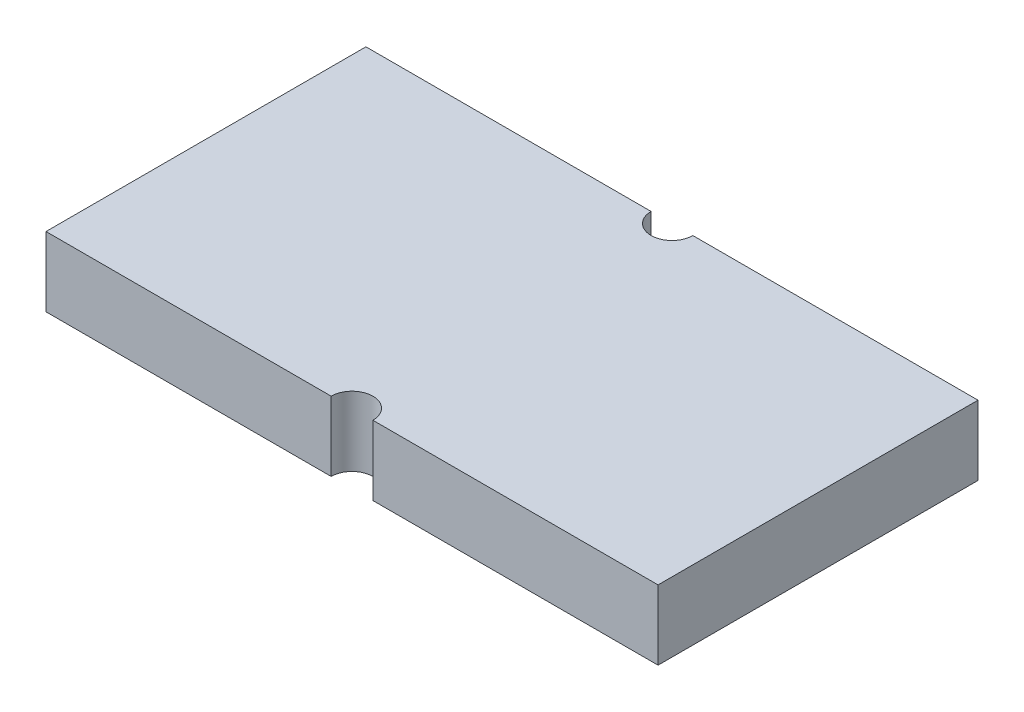
SolidWorks part; units mm, degrees
material "ABS"
ref_plane "前视基准面" through (0, 0, 0) normal (0, 0, 1) x (1, 0, 0)
ref_plane "上视基准面" through (0, 0, 0) normal (0, 1, 0) x (1, 0, 0)
ref_plane "右视基准面" through (0, 0, 0) normal (1, 0, 0) x (0, 0, -1)
sketch "草图1" plane through (0, 0, 0) normal (0, 1, 0) x (1, 0, 0)
  line L1 (-22, -11.5) -> (22, -11.5)
  line L2 (-22, -11.5) -> (-22, 11.5)
  line L3 (-22, 11.5) -> (22, 11.5)
  line L4 (22, -11.5) -> (22, 11.5)
  line L5 (-22, -11.5) -> (22, 11.5) construction
  line L6 (-22, 11.5) -> (22, -11.5) construction
  point P0 (0, 0)
  dimension "D1" = 44
  dimension "D2" = 23
extrude "凸台-拉伸1" add sketch "草图1" along normal blind 5
sketch "草图2" plane through (0, 5, 0) normal (0, 1, 0) x (1, 0, 0)
  line L0 (22, 11.5) -> (-22, 11.5) construction
  line L1 (-22, -11.5) -> (22, -11.5) construction
  circle A0 centre (0, 11.5) radius 1.5
  circle A1 centre (0, -11.5) radius 1.5
  dimension "D1" = 3
extrude "切除-拉伸1" cut sketch "草图2" against normal blind 10
